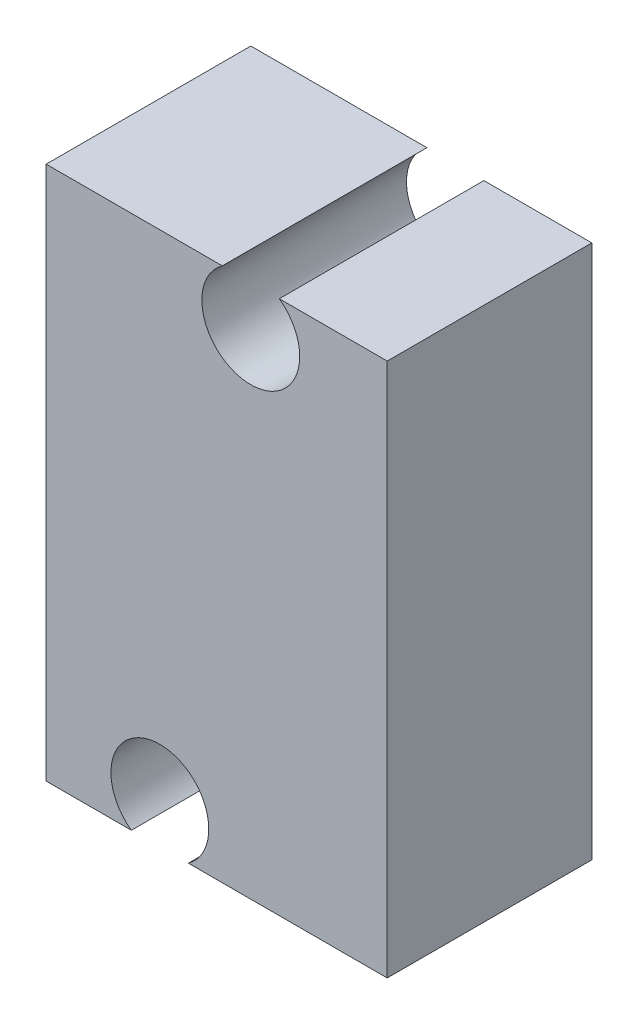
SolidWorks part; units mm, degrees
ref_plane "Front Plane" through (0, 0, 0) normal (0, 0, 1) x (1, 0, 0)
ref_plane "Top Plane" through (0, 0, 0) normal (0, 1, 0) x (1, 0, 0)
ref_plane "Right Plane" through (0, 0, 0) normal (1, 0, 0) x (0, 0, -1)
sketch "Sketch1" plane through (0, 0, 0) normal (0, 0, 1) x (1, 0, 0)
  line L1 (-9.1179, 10.8276) -> (9.9321, 10.8276)
  line L2 (-9.1179, 10.8276) -> (-9.1179, -19.0174)
  line L3 (-9.1179, -19.0174) -> (9.9321, -19.0174)
  line L4 (9.9321, 10.8276) -> (9.9321, -19.0174)
  dimension "D1" = 19.05
  dimension "D2" = 29.845
extrude "Boss-Extrude1" add sketch "Sketch1" along normal blind 11.43
sketch "Sketch2" plane through (0, 0, 11.43) normal (0, 0, 1) x (1, 0, 0)
  line L1 (-9.1179, 10.8276) -> (-9.1179, -19.0174) construction
  line L2 (-9.1179, -19.0174) -> (9.9321, -19.0174) construction
  circle A0 centre (2.3121, 8.6051) radius 2.7333
  circle A1 centre (-2.7679, -16.7949) radius 2.7333
  dimension "D1" = 25.4
  dimension "D2" = 5.08
  dimension "D3" = 6.35
  dimension "D4" = 2.2225
extrude "Cut-Extrude1" cut sketch "Sketch2" against normal blind 11.43
